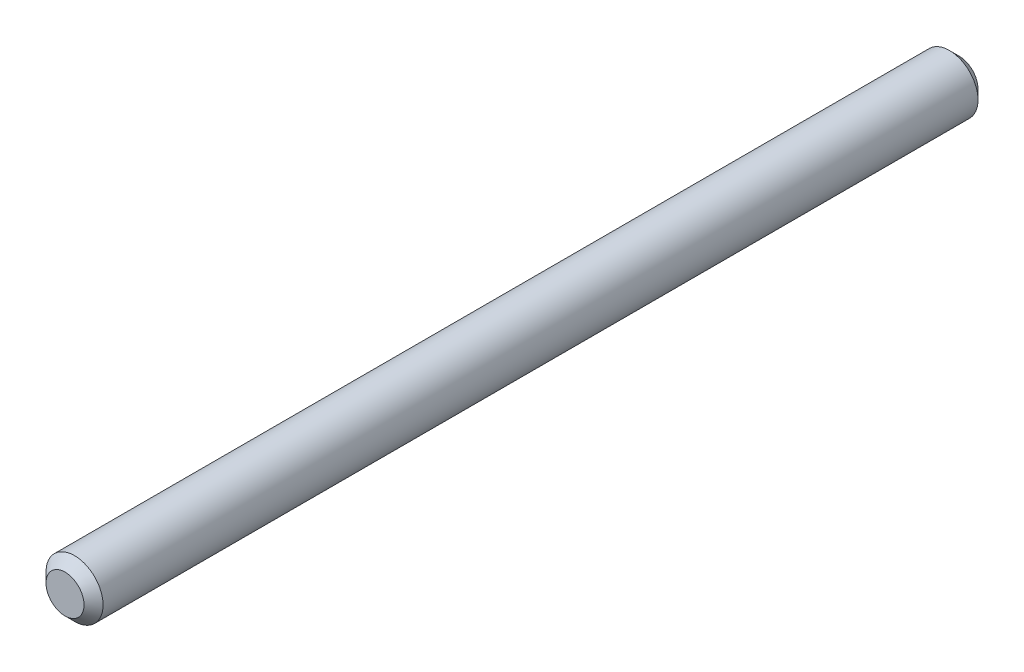
SolidWorks part; units mm, degrees
ref_plane "Front Plane" through (0, 0, 0) normal (0, 0, 1) x (1, 0, 0)
ref_plane "Top Plane" through (0, 0, 0) normal (0, 1, 0) x (1, 0, 0)
ref_plane "Right Plane" through (0, 0, 0) normal (1, 0, 0) x (0, 0, -1)
sketch "Sketch1" plane through (0, 0, 0) normal (0, 0, 1) x (1, 0, 0)
  circle A0 centre (0, 0) radius 1.5
extrude "Boss-Extrude1" add sketch "Sketch1" along normal blind 40 and the other way blind 7 contours A0
chamfer "Chamfer1" distance 0.5 angle 45 2 edges at (1.5, 0, -7) (1.5, 0, 40)
ref_plane "Plane1" through (0, 0, 16.5) normal (0, 0, 1) x (1, 0, 0)
sketch "Sketch2" plane through (0, 0, 16.5) normal (0, 0, 1) x (1, 0, 0)
  circle A0 centre (0, 0) radius 1
extrude "Cut-Extrude1" cut sketch "Sketch2" along normal blind 1 and the other way blind 1
